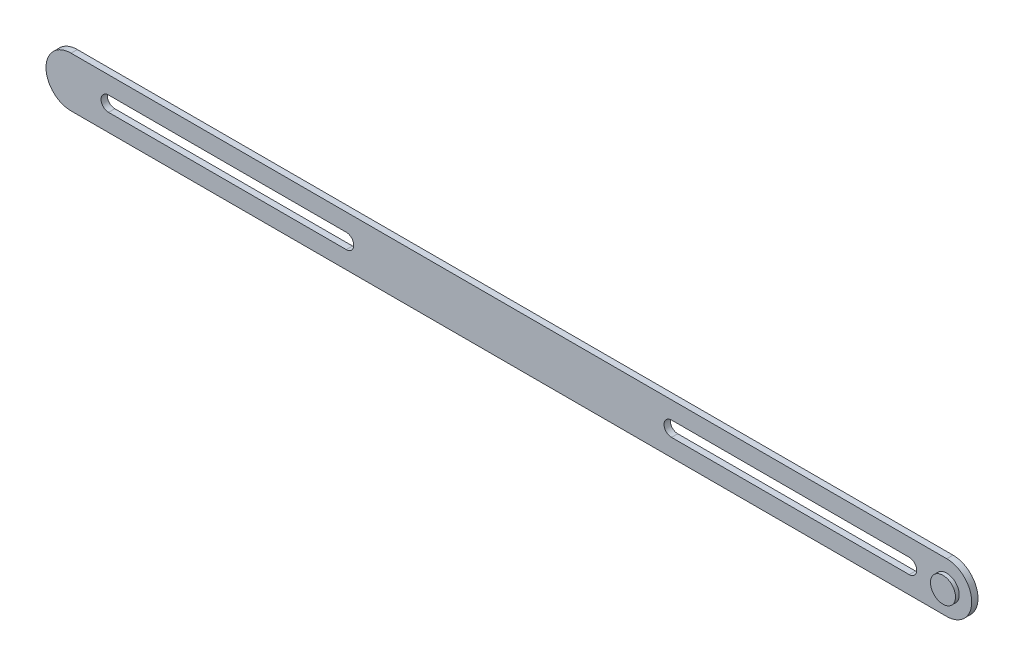
SolidWorks part; units mm, degrees
ref_plane "Front Plane" through (0, 0, 0) normal (0, 0, 1) x (1, 0, 0)
ref_plane "Top Plane" through (0, 0, 0) normal (0, 1, 0) x (1, 0, 0)
ref_plane "Right Plane" through (0, 0, 0) normal (1, 0, 0) x (0, 0, -1)
sketch "Sketch1" plane through (0, 0, 0) normal (0, 0, 1) x (1, 0, 0)
  circle A0 centre (0, 0) radius 2.5
  dimension "D1" = 5
extrude "Boss-Extrude1" add sketch "Sketch1" along normal blind 4
sketch "Sketch3" plane through (0, 0, 4) normal (0, 0, 1) x (1, 0, 0)
  line L0 (0, 0) -> (350, 0) construction
  line L1 (0, 10) -> (350, 10)
  line L2 (0, -10) -> (350, -10)
  line L3 (15, 0) -> (110, 0) construction
  line L4 (15, 3) -> (110, 3)
  line L5 (15, -3) -> (110, -3)
  line L6 (175, 0) -> (175, 22.7191) construction
  line L7 (175, 22.7191) -> (175, 0) construction
  line L8 (175, 0) -> (175, -20.6936) construction
  line L9 (335, 0) -> (240, 0) construction
  line L10 (335, 3) -> (240, 3)
  line L11 (335, -3) -> (240, -3)
  arc A0 (0, 10) -> (0, -10) centre (0, 0) ccw
  arc A1 (350, -10) -> (350, 10) centre (350, 0) ccw
  arc A2 (15, 3) -> (15, -3) centre (15, 0) ccw
  arc A3 (110, -3) -> (110, 3) centre (110, 0) ccw
  circle A4 centre (350, 0) radius 5
  arc A5 (335, 3) -> (335, -3) centre (335, 0) cw
  arc A6 (240, -3) -> (240, 3) centre (240, 0) cw
  circle A7 centre (0, 0) radius 2.5 construction
  point P3 (175, 0)
  point P10 (62.5, 0)
  point P22 (287.5, 0)
  dimension "D2" = 10
  dimension "D5" = 3
  dimension "D6" = 10
  dimension "D1" = 350
  dimension "D3" = 95
  dimension "D4" = 15
extrude "Boss-Extrude2" add sketch "Sketch3" along normal blind 2.5
sketch "Sketch4" plane through (0, 0, 4) normal (0, 0, -1) x (-1, 0, 0)
  circle A0 centre (-350, 0) radius 5 construction
  circle A1 centre (-350, 0) radius 5
extrude "Boss-Extrude3" add sketch "Sketch4" along normal blind 3.5 and the other way blind 4
